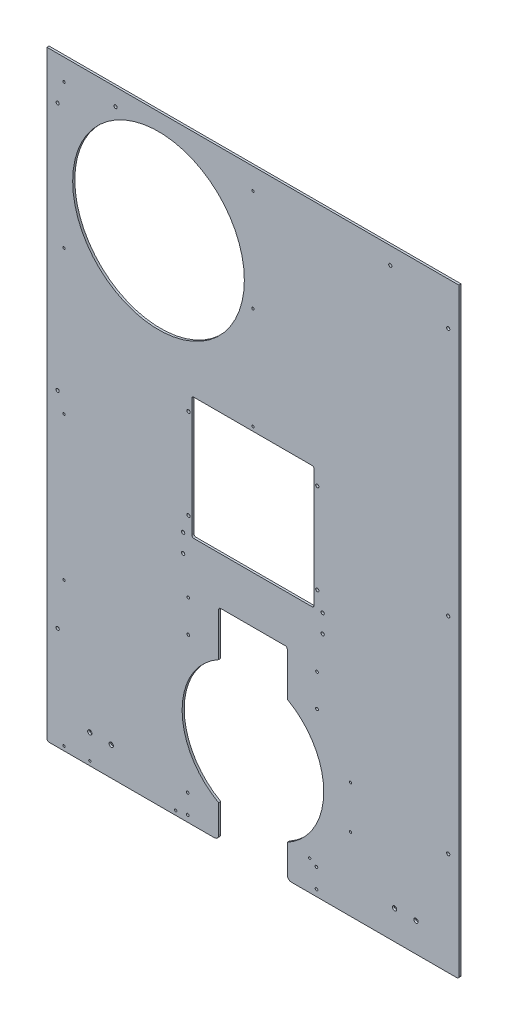
SolidWorks part; units mm, degrees
material "PC High Viscosity"
ref_plane "Front Plane" through (0, 0, 0) normal (0, 0, 1) x (1, 0, 0)
ref_plane "Top Plane" through (0, 0, 0) normal (0, 1, 0) x (1, 0, 0)
ref_plane "Right Plane" through (0, 0, 0) normal (1, 0, 0) x (0, 0, -1)
sketch "Sketch1" plane through (0, 0, 0) normal (0, 0, 1) x (1, 0, 0)
  line L2 (0, 0) -> (0, 1778)
  line L3 (0, 1778) -> (1219.2, 1778)
  line L4 (1219.2, 0) -> (1219.2, 1778)
  line L5 (428.625, 736.6) -> (790.575, 736.6)
  line L6 (428.625, 736.6) -> (428.625, 1098.55)
  line L7 (428.625, 1098.55) -> (790.575, 1098.55)
  line L8 (790.575, 736.6) -> (790.575, 1098.55)
  line L15 (0, 0) -> (1219.2, 0)
  circle A1 centre (330.2, 1473.2) radius 254
  point P7 (609.6, 1098.55)
  dimension "D3" = 736.6
  dimension "D6" = 508
  dimension "D7" = 330.2
  dimension "D1" = 1219.2
  dimension "D2" = 1778
  dimension "D4" = 361.95
  dimension "D5" = 609.6
  dimension "D8" = 1473.2
extrude "Boss-Extrude1" add sketch "Sketch1" along normal blind 6.35
sketch "Sketch3" plane through (0, 0, 6.35) normal (0, 0, 1) x (1, 0, 0)
  line L0 (0, 0) -> (1219.2, 0) construction
  line L2 (428.625, 736.6) -> (790.575, 736.6) construction
  circle A0 centre (609.6, 279.4) radius 209.55
  point P5 (609.6, 736.6)
  dimension "D1" = 419.1
  dimension "D2" = 279.4
extrude "Cut-Extrude2" cut sketch "Sketch3" against normal through all
sketch "Sketch2" plane through (0, 0, 6.35) normal (0, 0, 1) x (1, 0, 0)
  line L1 (508, 127) -> (711.2, 127)
  line L2 (508, 127) -> (508, -38.1)
  line L3 (508, -38.1) -> (711.2, -38.1)
  line L4 (711.2, 127) -> (711.2, -38.1)
  line L6 (508, 596.9) -> (711.2, 596.9)
  line L7 (508, 596.9) -> (508, 431.8)
  line L8 (508, 431.8) -> (711.2, 431.8)
  line L9 (711.2, 596.9) -> (711.2, 431.8)
  line L10 (790.575, 1098.55) -> (428.625, 1098.55) construction
  circle A0 centre (609.6, 279.4) radius 241.3 construction
  point P12 (609.6, 596.9)
  point P15 (609.6, 1098.55)
  point P16 (609.6, -38.1)
  point P17 (609.6, 431.8)
  dimension "D3" = 482.6
  dimension "D4" = 165.1
  dimension "D2" = 317.5
  dimension "D5" = 317.5
  dimension "D1" = 203.2
  dimension "D6" = 165.1
extrude "Cut-Extrude1" cut sketch "Sketch2" against normal through all
sketch "Sketch4" plane through (0, 0, 6.35) normal (0, 0, 1) x (1, 0, 0)
  line L1 (0, 0) -> (508, 0) construction
  line L6 (0, 1778) -> (0, 0) construction
  circle A0 centre (50.8, 12.7) radius 3.3655
  dimension "D1" = 6.731
  dimension "D2" = 12.7
  dimension "D3" = 50.8
extrude "Cut-Extrude3" cut sketch "Sketch4" against normal through all
pattern_linear "LPattern1" count 5 spacing 425.45 along (0, 1, 0) of "Cut-Extrude3"
sketch "Sketch5" plane through (0, 0, 6.35) normal (0, 0, 1) x (1, 0, 0)
  line L0 (1219.2, 1778) -> (0, 1778) construction
  line L1 (0, 1778) -> (0, 0) construction
  circle A0 centre (609.6, 1714.5) radius 3.429
  dimension "D1" = 63.5
  dimension "D2" = 6.858
  dimension "D3" = 609.6
extrude "Cut-Extrude4" cut sketch "Sketch5" against normal through all
pattern_linear "LPattern2" count 3 spacing 301.625 along (0, -1, 0) of "Cut-Extrude4"
sketch "Sketch6" plane through (0, 0, 6.35) normal (0, 0, 1) x (1, 0, 0)
  line L0 (0, 0) -> (508, 0) construction
  line L2 (0, 1778) -> (0, 0) construction
  circle A0 centre (127, 12.7) radius 3.3782
  circle A1 centre (381, 12.7) radius 3.3782
  dimension "D1" = 12.7
  dimension "D3" = 6.7564
  dimension "D2" = 254
  dimension "D4" = 127
extrude "Cut-Extrude5" cut sketch "Sketch6" against normal through all
sketch "Sketch7" plane through (0, 0, 6.35) normal (0, 0, 1) x (1, 0, 0)
  line L1 (711.2, 0) -> (1219.2, 0) construction
  circle A0 centre (777.6052, 88.9) radius 3.3782
  circle A1 centre (609.6, 279.4) radius 241.3 construction
  circle A2 centre (777.6052, 88.9) radius 12.7 construction
  circle A3 centre (609.6, 279.4) radius 254 construction
  circle A4 centre (898.525, 342.9) radius 3.3782
  circle A5 centre (898.525, 215.9) radius 3.3782
  dimension "D1" = 63.5
  dimension "D3" = 6.7564
  dimension "D4" = 482.6
  dimension "D5" = 25.4
  dimension "D6" = 508
  dimension "D2" = 88.9
  dimension "D7" = 127
  dimension "D12" = 288.925
  dimension "D13" = 215.9
extrude "Cut-Extrude6" cut sketch "Sketch7" against normal through all contours A4 | A5 | A0
sketch "Sketch9" plane through (0, 0, 6.35) normal (0, 0, 1) x (1, 0, 0)
  line L0 (0, 0) -> (508, 0) construction
  line L1 (0, 1778) -> (0, 0) construction
  point P0 (127, 85.725)
  point P1 (190.5, 85.725)
  dimension "D1" = 63.5
  dimension "D2" = 85.725
  dimension "D3" = 127
hole_wizard "CSK for 1/4 Flat Head Machine Screw1" positions "Sketch10" profile "Sketch11" countersink size "1/4" standard "ANSI Inch" end condition through all
sketch "Sketch10" plane through (0, 0, 6.35) normal (0, 0, 1) x (1, 0, 0)
  point P0 (127, 85.725)
  point P3 (190.5, 85.725)
sketch "Sketch11" plane through (127, 85.725, 6.35) normal (1, 0, 0) x (0, -1, 0)
  line L0 (0, 0) -> (0, 6.35)
  line L1 (0, 6.35) -> (3.5712, 6.35)
  line L2 (3.5712, 6.35) -> (3.5712, 3.2989)
  line L3 (3.5712, 3.2989) -> (6.4389, 0)
  line L5 (6.4389, 0) -> (0, 0)
  line L6 (-3.5712, 3.2989) -> (-6.4389, 0) construction
  line L11 (0, -6.35) -> (0, 107.95) construction
  dimension "Thru Hole Dia." = 7.1425
  dimension "Thru Hole Depth" = 6.35
  dimension "Near C'Sink Dia." = 12.8778
  dimension "Near C'Sink Angle" = 82
pattern_linear "LPattern3" count 2 spacing 901.7 along (1, 0, 0) of "CSK for 1/4 Flat Head Machine Screw1"
sketch "Sketch12" plane through (0, 0, 6.35) normal (0, 0, 1) x (1, 0, 0)
  line L0 (0, 1778) -> (0, 0) construction
  line L1 (1219.2, 0) -> (1219.2, 1778) construction
  line L2 (1219.2, 1778) -> (0, 1778) construction
  circle A0 centre (203.2, 1727.2) radius 4.7625
  circle A1 centre (1016, 1727.2) radius 4.7625
  dimension "D1" = 203.2
  dimension "D4" = 9.525
  dimension "D2" = 203.2
  dimension "D3" = 50.8
extrude "Cut-Extrude7" cut sketch "Sketch12" against normal through all
ref_plane "Plane1" through (609.6, 0, 0) normal (-1, 0, 0) x (0, 0, 1)
sketch "Sketch14" plane through (0, 0, 6.35) normal (0, 0, 1) x (1, 0, 0)
  line L0 (0, 1778) -> (0, 0) construction
  line L1 (1219.2, 1778) -> (0, 1778) construction
  line L2 (0, 0) -> (508, 0) construction
  circle A0 centre (31.75, 1651) radius 4.7625
  circle A1 centre (31.75, 914.4) radius 4.7625
  circle A2 centre (31.75, 304.8) radius 4.7625
  dimension "D1" = 31.75
  dimension "D2" = 9.525
  dimension "D3" = 127
  dimension "D4" = 304.8
  dimension "D5" = 914.4
extrude "Cut-Extrude8" cut sketch "Sketch14" against normal through all
mirror "Mirror1" about plane through (609.6, 0, 0) normal (-1, 0, 0) of "Cut-Extrude8"
sketch "Sketch15" plane through (0, 0, 6.35) normal (0, 0, 1) x (1, 0, 0)
  line L0 (428.625, 736.6) -> (790.575, 736.6) construction
  line L1 (428.625, 1098.55) -> (428.625, 736.6) construction
  circle A0 centre (403.225, 736.6) radius 4.7625
  circle A1 centre (403.225, 682.625) radius 4.7625
  dimension "D1" = 53.975
  dimension "D3" = 9.525
  dimension "D2" = 25.4
extrude "Cut-Extrude9" cut sketch "Sketch15" against normal through all
mirror "Mirror2" about plane through (609.6, 0, 0) normal (-1, 0, 0) of "Cut-Extrude9"
sketch "Sketch16" plane through (0, 0, 6.35) normal (0, 0, 1) x (1, 0, 0)
  line L0 (428.625, 1098.55) -> (428.625, 736.6) construction
  line L1 (428.625, 736.6) -> (790.575, 736.6) construction
  line L2 (790.575, 736.6) -> (790.575, 1098.55) construction
  circle A0 centre (419.1, 1054.1) radius 4.7625
  circle A1 centre (419.1, 787.4) radius 4.7625
  circle A2 centre (800.1, 1054.1) radius 4.7625
  circle A3 centre (800.1, 787.4) radius 4.7625
  dimension "D1" = 9.525
  dimension "D2" = 9.525
  dimension "D3" = 266.7
  dimension "D4" = 50.8
  dimension "D5" = 9.525
extrude "Cut-Extrude10" cut sketch "Sketch16" against normal through all
fillet "Fillet1" radius 12.7 2 edges at (711.2, 0, 3.175) (508, 0, 3.175)
fillet "Fillet2" radius 6.35 8 edges at (508, 596.9, 3.175) (711.2, 596.9, 3.175) (790.575, 736.6, 3.175) (790.575, 1098.55, 3.175) (428.625, 1098.55, 3.175) (428.625, 736.6, 3.175) (0, 0, 3.175) (1219.2, 0, 3.175)
sketch "Sketch17" plane through (0, 0, 6.35) normal (0, 0, 1) x (1, 0, 0)
  line L0 (44.45, 0) -> (463.55, 0) construction
  line L1 (0, 1778) -> (0, 6.35) construction
  circle A4 centre (416.5676, 76.2) radius 3.937
  circle A5 centre (416.5676, 19.05) radius 3.937
  circle A6 centre (797.5676, 19.05) radius 3.937
  circle A7 centre (797.5676, 76.2) radius 3.937
  point P8 (0, 0)
  point P9 (0, 0)
  point P10 (0, 0)
  point P15 (0, 0)
  dimension "D3" = 381
  dimension "D4" = 19.05
  dimension "D1" = 7.874
  dimension "D2" = 57.15
  dimension "D5" = 416.5676
extrude "Cut-Extrude11" cut sketch "Sketch17" against normal through all
sketch "Sketch18" plane through (0, 0, 6.35) normal (0, 0, 1) x (1, 0, 0)
  line L0 (0, 1778) -> (0, 6.35) construction
  line L1 (723.9, 0) -> (1212.85, 0) construction
  circle A0 centre (418.1551, 576.972) radius 3.9687
  circle A1 centre (418.1551, 481.722) radius 3.9687
  circle A2 centre (799.1551, 481.722) radius 3.9687
  circle A3 centre (799.1551, 576.972) radius 3.9687
  dimension "D2" = 7.9375
  dimension "D1" = 95.25
  dimension "D3" = 381
  dimension "D4" = 418.1551
  dimension "D5" = 481.722
extrude "Cut-Extrude12" cut sketch "Sketch18" against normal through all
